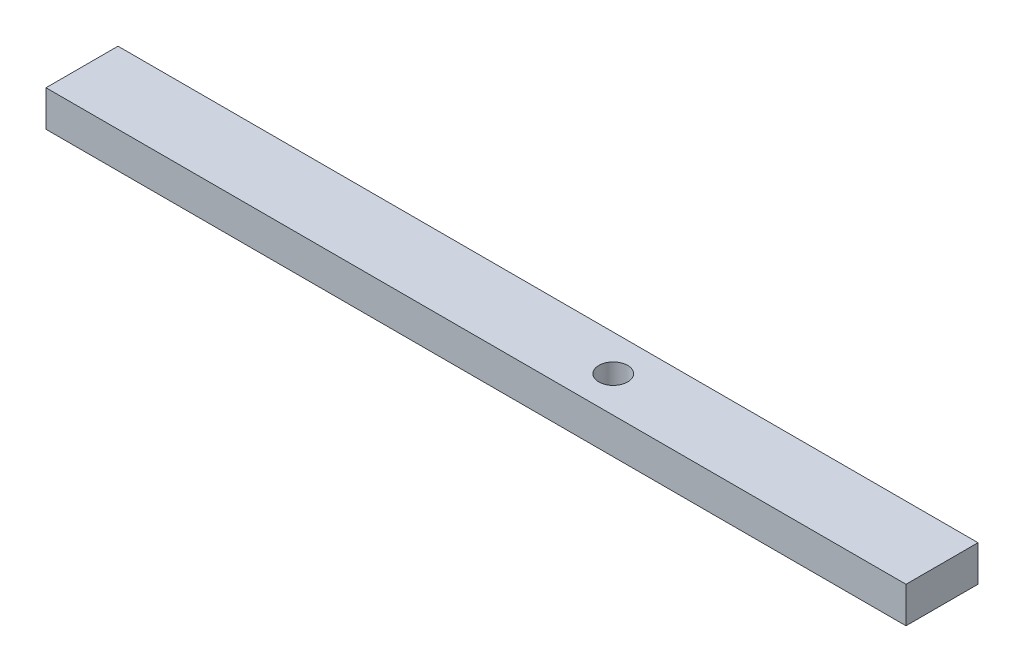
SolidWorks part; units mm, degrees
ref_plane "Front Plane" through (0, 0, 0) normal (0, 0, 1) x (1, 0, 0)
ref_plane "Top Plane" through (0, 0, 0) normal (0, 1, 0) x (1, 0, 0)
ref_plane "Right Plane" through (0, 0, 0) normal (1, 0, 0) x (0, 0, -1)
sketch "Sketch1" plane through (0, 0, 0) normal (0, 1, 0) x (1, 0, 0)
  line L1 (-119.449, 10) -> (0, 10)
  line L2 (-119.449, 10) -> (-119.449, 0)
  line L3 (-119.449, 0) -> (0, 0)
  line L4 (0, 10) -> (0, 0)
  line L5 (-119.449, 10) -> (0, 0) construction
  line L6 (-119.449, 0) -> (0, 10) construction
  circle A0 centre (-45.6614, 5) radius 2
  point P0 (-59.7245, 5)
  dimension "D3" = 4
  dimension "D1" = 10
  dimension "D2" = 5
extrude "Boss-Extrude1" add sketch "Sketch1" along normal blind 5
sketch "Sketch3" plane through (0, 5, 0) normal (0, 1, 0) x (1, 0, 0)
  line L0 (-119.449, 0) -> (0, 0) construction
  line L1 (0, 0) -> (0, 10) construction
  point P0 (-5, 5)
  dimension "D1" = 5
  dimension "D2" = 5
sketch "Sketch4" plane through (0, 5, 0) normal (0, 1, 0) x (1, 0, 0)
  line L0 (0, 10) -> (-119.449, 10) construction
  line L1 (-119.449, 10) -> (-119.449, 0) construction
  point P0 (-114.449, 5)
  dimension "D1" = 5
  dimension "D2" = 5
